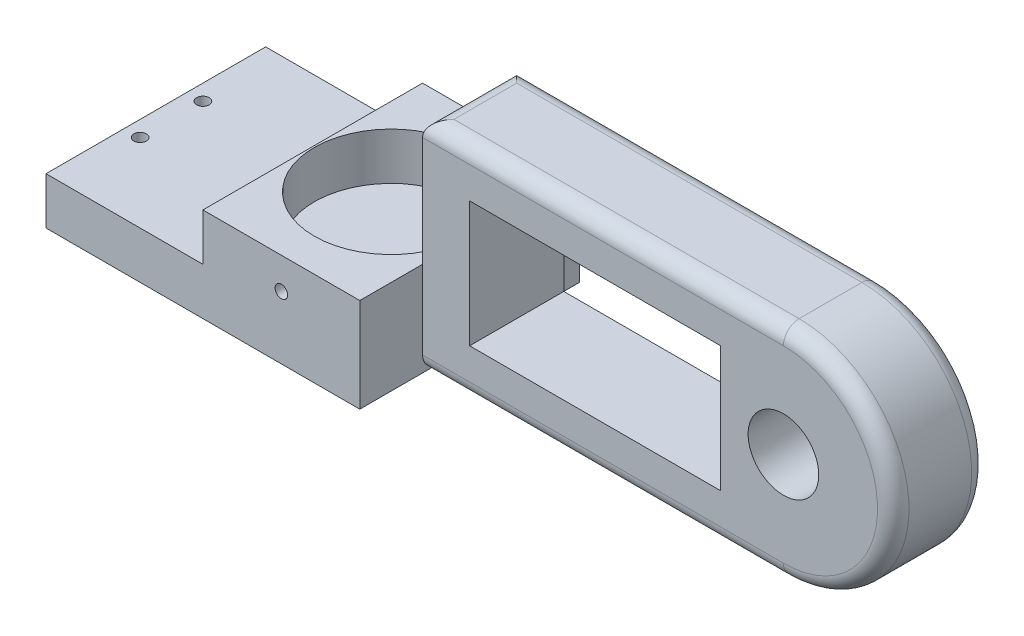
SolidWorks part; units mm, degrees
ref_plane "前视基准面" through (0, 0, 0) normal (0, 0, 1) x (1, 0, 0)
ref_plane "上视基准面" through (0, 0, 0) normal (0, 1, 0) x (1, 0, 0)
ref_plane "右视基准面" through (0, 0, 0) normal (1, 0, 0) x (0, 0, -1)
other "Configuration Table"
sketch "草图1" plane through (0, 0, 0) normal (0, 0, 1) x (1, 0, 0)
  line L1 (-150, -70) -> (150, -70)
  line L2 (-150, -70) -> (-150, 70)
  line L3 (-150, 70) -> (150, 70)
  line L4 (150, -70) -> (150, 70)
  line L5 (-150, -70) -> (150, 70) construction
  line L6 (-150, 70) -> (150, -70) construction
  point P0 (0, 0)
  dimension "D1" = 140
  dimension "D2" = 300
extrude "凸台-拉伸1" add sketch "草图1" along normal blind 60
sketch "草图2" plane through (0, 0, 60) normal (0, 0, 1) x (1, 0, 0)
  line L0 (-150, -70) -> (150, -70) construction
  line L1 (150, 70) -> (10, 70)
  line L2 (150, 70) -> (150, -70)
  line L3 (150, -70) -> (10, -70)
  line L4 (10, 70) -> (10, -70)
  line L5 (10, 70) -> (150, -70) construction
  circle A0 centre (80, 0) radius 70
  line M6 (150, -70) -> (150, 70)
  line M7 (150, 70) -> (-150, 70)
  dimension "D2" = 140
  dimension "D1" = 140
extrude "切除-拉伸1" cut sketch "草图2" against normal blind 60 contours A0 L2 M7 | L5 A0 L3 | A0 L5 M6
sketch "草图3" plane through (0, 0, 0) normal (0, 0, -1) x (-1, 0, 0)
  line L3 (-80, -70) -> (150, -70)
  line L4 (150, -70) -> (150, 70)
  line L5 (150, 70) -> (-80, 70)
  line L6 (-80, -70) -> (150, -70)
  line L7 (150, -70) -> (150, 70)
  line L8 (150, 70) -> (-80, 70)
  circle A0 centre (-80, 0) radius 25
  arc A1 (-80, 70) -> (-80, -70) centre (-80, 0) ccw
  arc A2 (-80, 70) -> (-80, -70) centre (-80, 0) ccw
  dimension "D2" = 50
  dimension "D1" = 0
sketch "草图4" plane through (0, 0, 60) normal (0, 0, 1) x (1, 0, 0)
  line L0 (80, 70) -> (-150, 70) construction
  line L1 (-120, 40) -> (40, 40)
  line L2 (-120, 40) -> (-120, -40)
  line L3 (-120, -40) -> (40, -40)
  line L4 (40, 40) -> (40, -40)
  line L5 (-150, -70) -> (80, -70) construction
  line L6 (-150, 70) -> (-150, -70) construction
  dimension "D1" = 30
  dimension "D2" = 30
  dimension "D3" = 30
  dimension "D4" = 160
extrude "切除-拉伸2" cut sketch "草图4" against normal through all
sketch "草图5" plane through (0, 0, 0) normal (0, 0, -1) x (-1, 0, 0)
  line L1 (-90, -10) -> (-70, -10)
  line L2 (-90, -10) -> (-90, 10)
  line L3 (-90, 10) -> (-70, 10)
  line L4 (-70, -10) -> (-70, 10)
  line L5 (-90, -10) -> (-70, 10) construction
  line L6 (-90, 10) -> (-70, -10) construction
  point P0 (-80, 0)
  dimension "D1" = 20
  dimension "D2" = 20
extrude "切除-拉伸3" cut sketch "草图5" against normal through all
sketch "草图12" plane through (-150, 0, 0) normal (-1, 0, 0) x (0, 0, 1)
  line L0 (0, -70) -> (0, 70) construction
  line L1 (-40, -70) -> (100, -70)
  line L2 (-40, -70) -> (-40, -40)
  line L3 (-40, -40) -> (100, -40)
  line L4 (100, -70) -> (100, -40)
  dimension "D1" = 140
  dimension "D2" = 30
  dimension "D3" = 40
extrude "凸台-拉伸2" add sketch "草图12" along normal blind 200
sketch "草图13" plane through (0, -40, 0) normal (0, 1, 0) x (1, 0, 0)
  line L0 (-350, -100) -> (-150, -100) construction
  line L1 (-150, 40) -> (-250, 40)
  line L2 (-150, 40) -> (-150, -100)
  line L3 (-150, -100) -> (-250, -100)
  line L4 (-250, 40) -> (-250, -100)
  dimension "D1" = 100
extrude "凸台-拉伸3" add sketch "草图13" along normal blind 30
sketch "草图14" plane through (0, -10, 0) normal (0, 1, 0) x (1, 0, 0)
  line L0 (-150, 40) -> (-250, -100) construction
  line L6 (-150, -100) -> (-150, -60)
  line L7 (-150, -60) -> (-150, 0)
  line L8 (-150, 0) -> (-150, 40)
  line L9 (-150, 40) -> (-250, 40)
  line L10 (-250, 40) -> (-250, -100)
  line L11 (-250, -100) -> (-150, -100)
  line L12 (-150, -100) -> (-150, -60)
  line L13 (-150, -60) -> (-150, 0)
  line L14 (-150, 0) -> (-150, 40)
  line L15 (-150, 40) -> (-250, 40)
  line L16 (-250, 40) -> (-250, -100)
  line L17 (-250, -100) -> (-150, -100)
  circle A1 centre (-200, -30) radius 49
  dimension "D2" = 98
  dimension "D1" = 0
extrude "切除-拉伸4" cut sketch "草图14" against normal blind 30 contours A1
sketch "草图15" plane through (0, -40, 0) normal (0, 1, 0) x (1, 0, 0)
  line L0 (-340, 40) -> (-340, -100)
  line L1 (-350, 40) -> (-250, 40) construction
  line L2 (-350, -100) -> (-250, -100) construction
  line L3 (-350, -100) -> (-350, 40) construction
  circle A0 centre (-340, -10) radius 4
  circle A1 centre (-340, -50) radius 4
  dimension "D2" = 8
  dimension "D3" = 8
  dimension "D1" = 10
  dimension "D4" = 50
  dimension "D5" = 50
extrude "切除-拉伸5" cut sketch "草图15" against normal blind 30 contours L0 A1 | L0 A1 | L0 A0 | L0 A0
fillet "圆角3" radius 10 7 edges at (-35, -70, 60) (150, 0, 60) (-35, -70, 0) (150, 0, 0) (-35, 70, 60) (-150, 70, 30) (-35, 70, 0)
sketch "草图17" plane through (0, 0, 60) normal (0, 0, 1) x (1, 0, 0)
  circle A0 centre (80, 0) radius 22.5
  dimension "D1" = 45
extrude "切除-拉伸6" cut sketch "草图17" against normal blind 49.178
sketch "草图18" plane through (0, 0, 10.822) normal (0, 0, 1) x (1, 0, 0)
  circle A0 centre (80, 0) radius 17.5
  circle A1 centre (80, 17.5) radius 1.5
  circle A2 centre (95.1554, 8.75) radius 1.5
  circle A3 centre (95.1554, -8.75) radius 1.5
  circle A4 centre (80, -17.5) radius 1.5
  circle A5 centre (64.8446, -8.75) radius 1.5
  circle A6 centre (64.8446, 8.75) radius 1.5
  point P17 (80, 0)
  dimension "D1" = 35
  dimension "D2" = 3
  dimension "D3" = 6
extrude "切除-拉伸7" cut sketch "草图18" against normal blind 50 and the other way through all contours A0 A1 | A6 | A5 | A4 | A2 | A3
sketch "草图19" plane through (0, 0, 100) normal (0, 0, 1) x (1, 0, 0)
  line L0 (-250, -30) -> (-150, -30)
  line L1 (-150, -70) -> (-150, 70) construction
  line L2 (-250, -10) -> (-250, -40) construction
  line L3 (-250, -10) -> (-150, -10) construction
  circle A0 centre (-200, -30) radius 4
  point P7 (0, 0)
  point P8 (-250, -34.8157)
  dimension "D1" = 8
  dimension "D2" = 20
extrude "切除-拉伸8" cut sketch "草图19" against normal through all contours L0 A0
